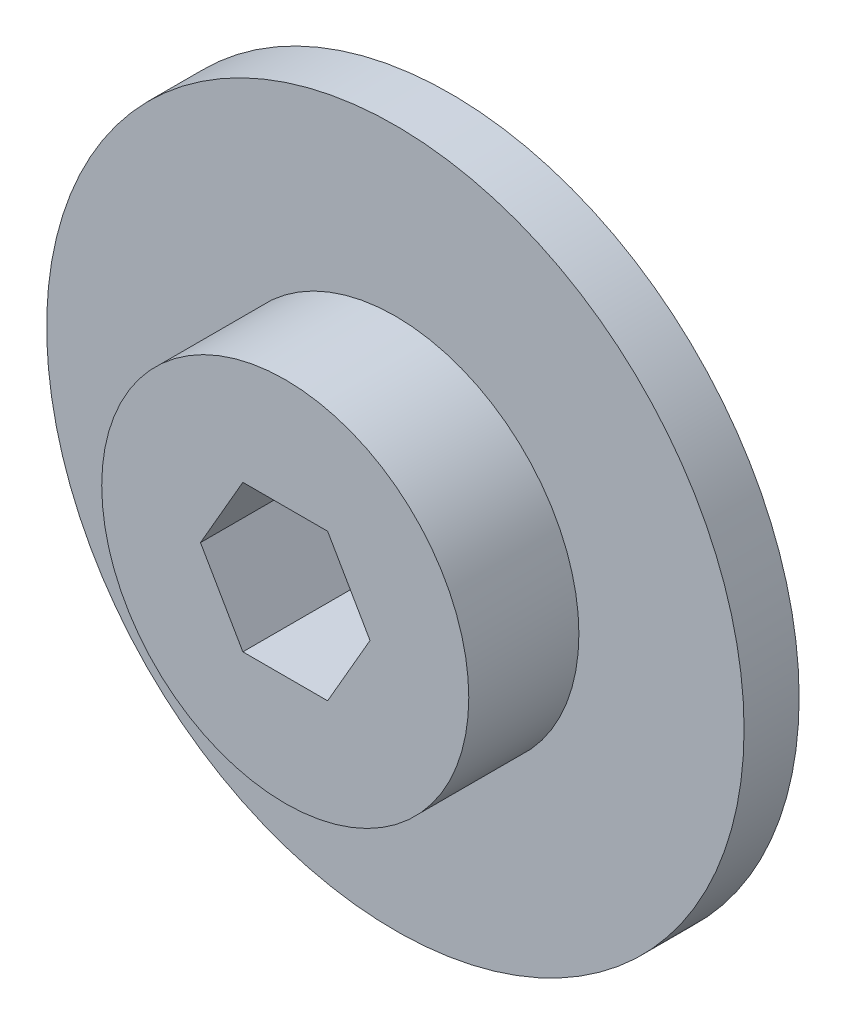
SolidWorks part; units mm, degrees
ref_plane "前视基准面" through (0, 0, 0) normal (0, 0, 1) x (1, 0, 0)
ref_plane "上视基准面" through (0, 0, 0) normal (0, 1, 0) x (1, 0, 0)
ref_plane "右视基准面" through (0, 0, 0) normal (1, 0, 0) x (0, 0, -1)
sketch "草图1" plane through (0, 0, 0) normal (0, 0, 1) x (1, 0, 0)
  circle A0 centre (0, 0) radius 9.5
  dimension "D1" = 19
extrude "凸台-拉伸1" add sketch "草图1" along normal blind 1.5
sketch "草图2" plane through (0, 0, 1.5) normal (0, 0, 1) x (1, 0, 0)
  circle A0 centre (0, 0) radius 5
  dimension "D1" = 10
extrude "凸台-拉伸2" add sketch "草图2" along normal blind 3
sketch "草图3" plane through (0, 0, 4.5) normal (0, 0, 1) x (1, 0, 0)
  line L1 (1.1547, 2) -> (-1.1547, 2)
  line L2 (-1.1547, 2) -> (-2.3094, 0)
  line L3 (-2.3094, 0) -> (-1.1547, -2)
  line L4 (-1.1547, -2) -> (1.1547, -2)
  line L5 (1.1547, -2) -> (2.3094, 0)
  line L6 (2.3094, 0) -> (1.1547, 2)
  circle A0 centre (0, 0) radius 2 construction
  dimension "D1" = 4
extrude "切除-拉伸1" cut sketch "草图3" against normal blind 3
